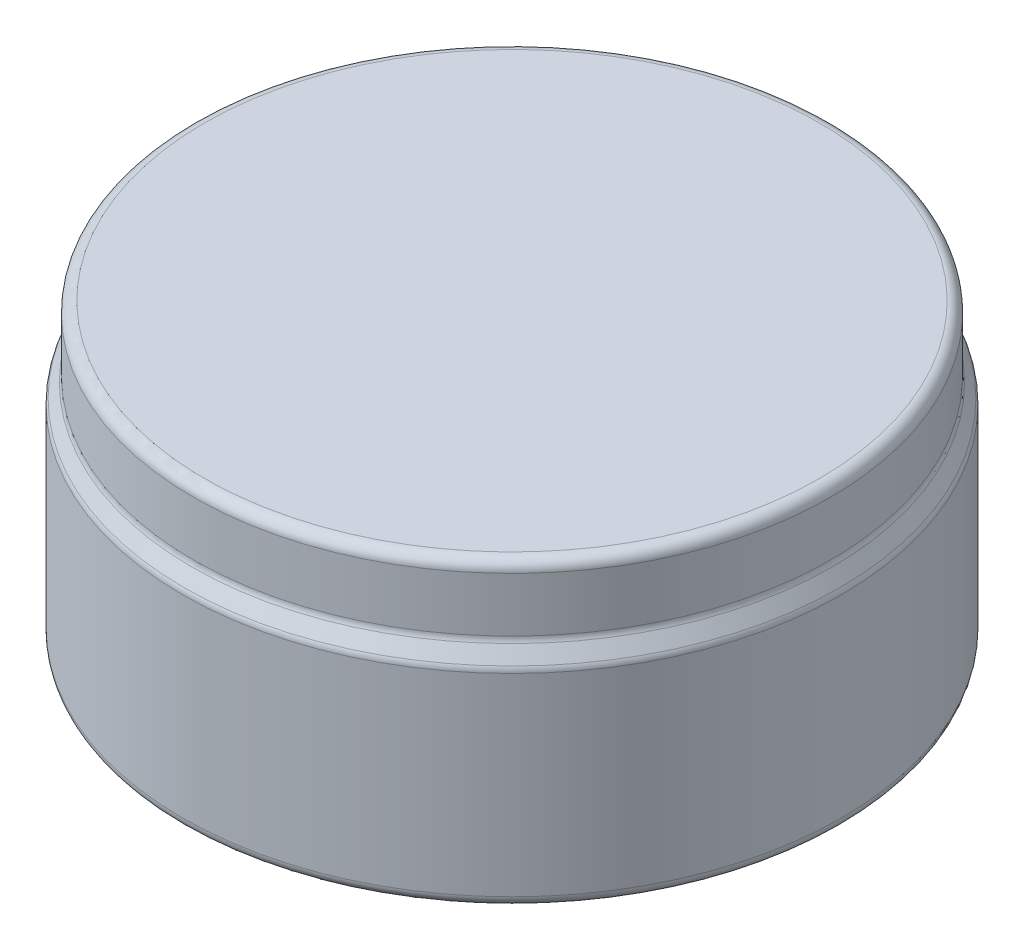
SolidWorks part; units mm, degrees
ref_plane "Front Plane" through (0, 0, 0) normal (0, 0, 1) x (1, 0, 0)
ref_plane "Top Plane" through (0, 0, 0) normal (0, 1, 0) x (1, 0, 0)
ref_plane "Right Plane" through (0, 0, 0) normal (1, 0, 0) x (0, 0, -1)
sketch "Sketch1" plane through (0, 0, 0) normal (0, 0, 1) x (1, 0, 0)
  line L0 (0, 0) -> (-6.05, 0)
  line L1 (-6.05, 0) -> (-6.05, 3.8036)
  line L2 (-6.05, 3.8036) -> (-5.85, 4.15)
  line L3 (-5.85, 4.15) -> (-5.85, 5.2)
  line L4 (-5.65, 5.4) -> (0, 5.4)
  line L5 (0, 5.4) -> (0, 0)
  arc A0 (-5.85, 5.2) -> (-5.65, 5.4) centre (-5.65, 5.2) cw
  point P10 (-5.85, 5.4)
  dimension "D6" = 0.2
  dimension "D1" = 6.05
  dimension "D2" = 5.4
  dimension "D3" = 30
  dimension "D4" = 0.2
  dimension "D5" = 1.25
revolve "Revolve1" add sketch "Sketch1" angle 360 about L5
sketch "Sketch2" plane through (0, 0, 0) normal (0, 1, 0) x (1, 0, 0)
  line L0 (-0.5, -1.75) -> (-0.5, 1.75)
  line L1 (-0.5, 1.75) -> (3.2679, 1.75)
  line L2 (3.2679, 1.75) -> (5, 0.75)
  line L3 (5, 0.75) -> (5, -0.75)
  line L4 (-0.5, 0) -> (5, 0) construction
  line L5 (3.2679, -1.75) -> (5, -0.75)
  line L6 (-0.5, -1.75) -> (3.2679, -1.75)
  point P3 (-0.5, 0)
  dimension "D1" = 0.5
  dimension "D2" = 5
  dimension "D3" = 3.5
  dimension "D4" = 1.5
  dimension "D5" = 60
fillet "Fillet1" radius 0.2 1 edges at (-6.05, 0, 0)
fillet "Fillet2" radius 0.2 2 edges at (-5.85, 4.15, 0) (-6.05, 3.8036, 0)
